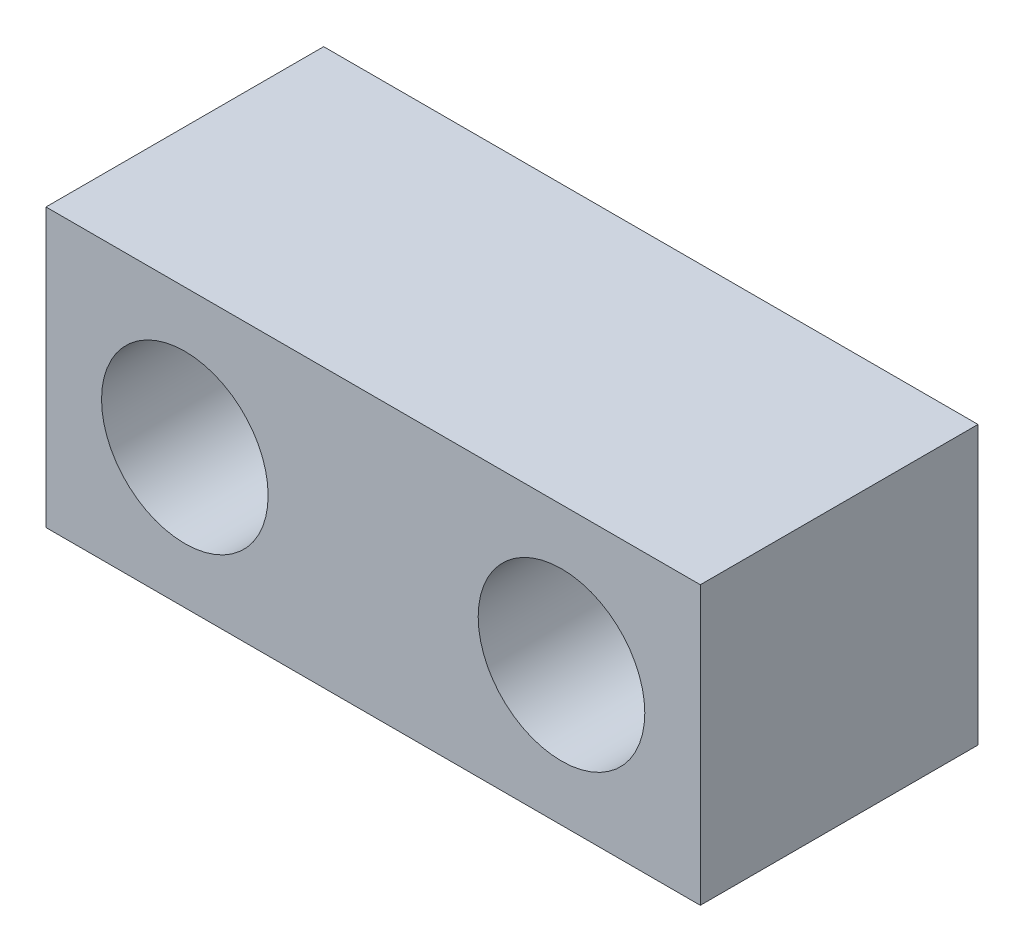
SolidWorks part; units mm, degrees
ref_plane "Front Plane" through (0, 0, 0) normal (0, 0, 1) x (1, 0, 0)
ref_plane "Top Plane" through (0, 0, 0) normal (0, 1, 0) x (1, 0, 0)
ref_plane "Right Plane" through (0, 0, 0) normal (1, 0, 0) x (0, 0, -1)
sketch "Sketch1" plane through (0, 0, 0) normal (0, 0, 1) x (1, 0, 0)
  line L1 (0, 0) -> (47.1297, 0)
  line L2 (0, 0) -> (0, 20)
  line L3 (0, 20) -> (47.1297, 20)
  line L4 (47.1297, 0) -> (47.1297, 20)
  dimension "D1" = 20
extrude "Extrude1" add sketch "Sketch1" along normal blind 20
hole_wizard "Ø12.0 (12) Diameter Hole1" positions "3DSketch3" profile "Sketch7" hole size "Ø12.0" standard "Ansi Metric" end condition through all
sketch3d "3DSketch3"
  line L0 (47.1297, 0, 20) -> (47.1297, 20, 20) construction
  line L1 (0, 20, 20) -> (0, 0, 20) construction
  line L2 (47.1297, 20, 20) -> (0, 20, 20) construction
  point P0 (37.1297, 10, 20)
  point P2 (10, 10, 20)
  dimension "D1" = 10
  dimension "D2" = 10
  dimension "D3" = 10
  dimension "D4" = 10
sketch "Sketch7" plane through (37.1297, 10, 20) normal (1, 0, 0) x (0, -1, 0)
  line L0 (0, 0) -> (0, 20)
  line L1 (0, 20) -> (6, 20)
  line L2 (6, 20) -> (6, 0)
  line L5 (6, 0) -> (0, 0)
  line L11 (0, -6.35) -> (0, 107.95) construction
  dimension "Thru Hole Dia." = 12
  dimension "Thru Hole Depth" = 20
